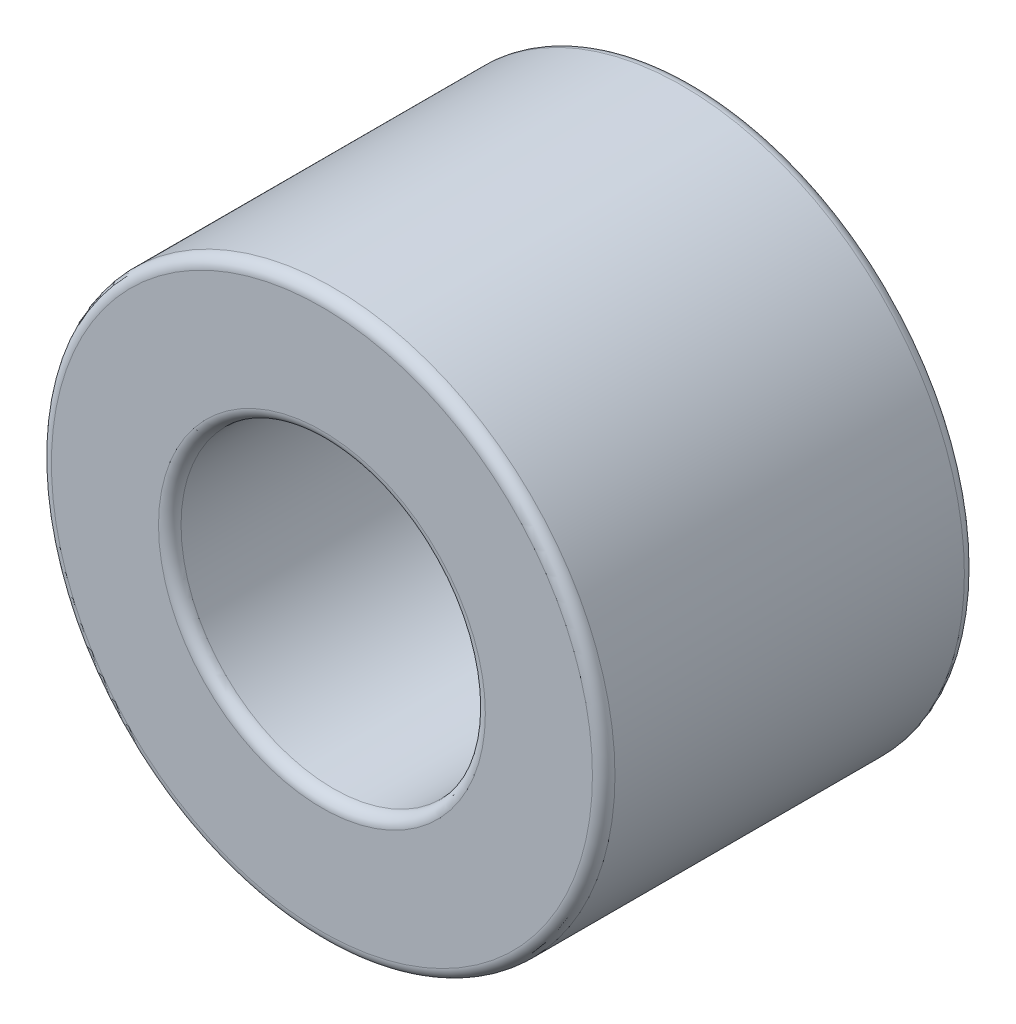
SolidWorks part; units mm, degrees
material "6061-T6 (SS)"
ref_plane "Front Plane" through (0, 0, 0) normal (0, 0, 1) x (1, 0, 0)
ref_plane "Top Plane" through (0, 0, 0) normal (0, 1, 0) x (1, 0, 0)
ref_plane "Right Plane" through (0, 0, 0) normal (1, 0, 0) x (0, 0, -1)
sketch "Sketch1" plane through (0, 0, 0) normal (0, 0, 1) x (1, 0, 0)
  circle A0 centre (0, 0) radius 1.7145
  circle A1 centre (0, 0) radius 3.175
  dimension "D1" = 6.35
  dimension "D2" = 3.429
extrude "Boss-Extrude1" add sketch "Sketch1" along normal blind 4.191
fillet "Fillet1" radius 0.127 4 edges at (1.7145, 0, 0) (3.175, 0, 0) (1.7145, 0, 4.191) (3.175, 0, 4.191)
